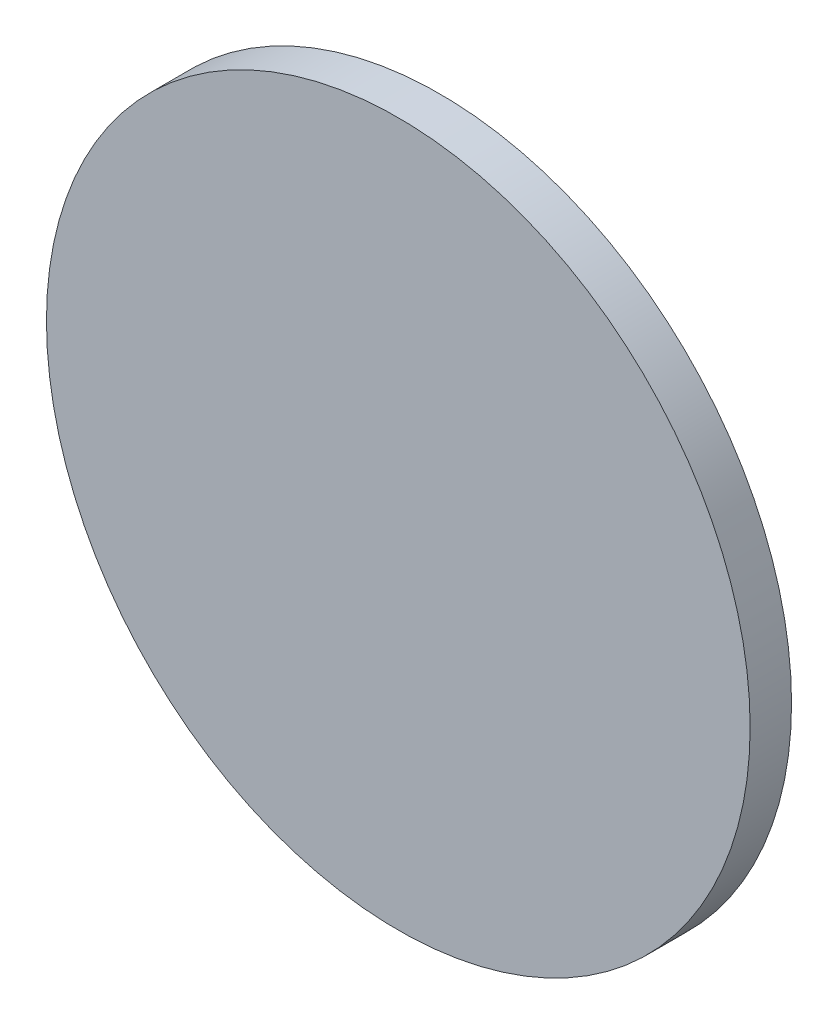
SolidWorks part; units mm, degrees
ref_plane "前视基准面" through (0, 0, 0) normal (0, 0, 1) x (1, 0, 0)
ref_plane "上视基准面" through (0, 0, 0) normal (0, 1, 0) x (1, 0, 0)
ref_plane "右视基准面" through (0, 0, 0) normal (1, 0, 0) x (0, 0, -1)
sketch "草图2" plane through (0, 0, 0) normal (0, 0, 1) x (1, 0, 0)
  circle A0 centre (0, 0) radius 34
  dimension "D1" = 68
extrude "凸台-拉伸1" add sketch "草图2" along normal blind 4
